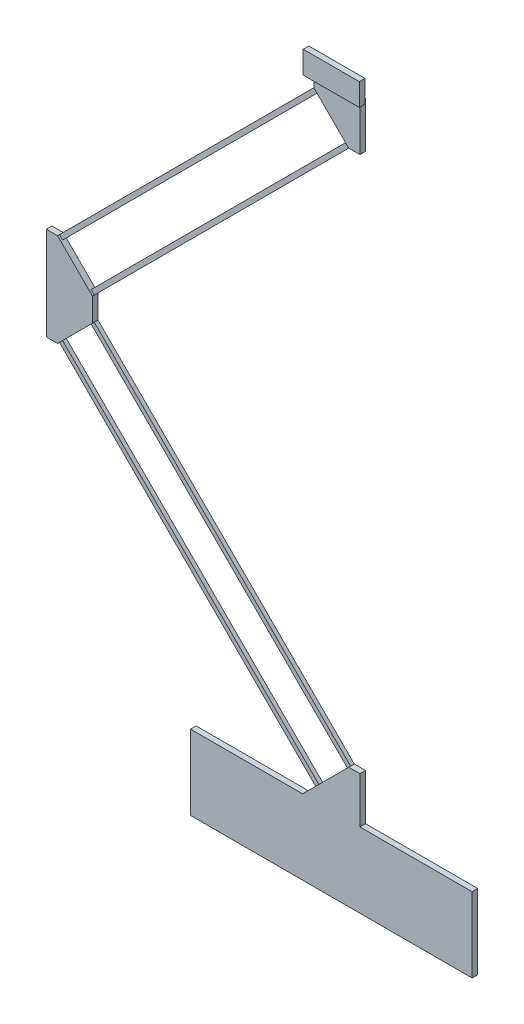
SolidWorks part; units mm, degrees
ref_plane "Front Plane" through (0, 0, 0) normal (0, 0, 1) x (1, 0, 0)
ref_plane "Top Plane" through (0, 0, 0) normal (0, 1, 0) x (1, 0, 0)
ref_plane "Right Plane" through (0, 0, 0) normal (1, 0, 0) x (0, 0, -1)
sketch "Sketch1" plane through (0, 0, 0) normal (0, 0, 1) x (1, 0, 0)
  line L0 (0, 0) -> (-84.8528, -84.8528)
  line L1 (0, 0) -> (-707.1068, 707.1068)
  line L2 (-84.8528, -84.8528) -> (-791.9596, 622.254)
  line L3 (-707.1068, 707.1068) -> (-791.9596, 622.254)
  line L4 (0, 0) -> (0, -84.8528) construction
  line L5 (0, -84.8528) -> (-84.8528, -84.8528) construction
  line L6 (-707.1068, 757.1068) -> (-791.9596, 841.9596)
  line L7 (-707.1068, 757.1068) -> (0, 1464.2136)
  line L8 (-791.9596, 841.9596) -> (-84.8528, 1549.0664)
  line L9 (0, 1464.2136) -> (-84.8528, 1549.0664)
  line L10 (-791.9596, 622.254) -> (-791.9596, 841.9596) construction
  line L11 (-707.1068, 707.1068) -> (-707.1068, 757.1068) construction
  line L12 (-707.1068, 732.1068) -> (-791.9596, 732.1068) construction
  point P12 (-1084.8528, 134.3981)
  point P13 (0, 0)
  point P14 (-1007.5691, 47.0134)
  point P15 (-1084.8528, 139.5688)
  point P16 (-1013.47, 286.1864)
  point P17 (0, 0)
  point P18 (152.8359, 878.8141)
  point P19 (39.4877, 109.7667)
  point P20 (-108.543, 914.8665)
  point P21 (-241.3606, 995.4355)
  point P22 (-38.2524, 1037.8463)
  point P23 (-117.549, 500.9334)
  point P24 (27.0087, 309.2042)
  point P25 (-1084.8522, 26.1452)
  point P26 (0, 99.2151)
  point P27 (-84.8528, 138.3372)
  point P28 (0, 0)
  point P29 (0, 0)
  point P30 (0, 0)
  point P31 (-998.3362, 431.8761)
  point P32 (656.1081, 992.4753)
  point P33 (-167.8514, 1497.8051)
  dimension "D1" = 1000
  dimension "D2" = 120
  dimension "D3" = 45
  dimension "D4" = 120
  dimension "D5" = 1000
  dimension "D6" = 90
  dimension "D7" = 50
  dimension "D8" = 45
  dimension "D9" = 45
extrude "Extrude-Thin1" add sketch "Sketch1" along normal blind 10 thin thin type mid plane wall 12
sketch "Sketch2" plane through (0, 0, 0) normal (0, 0, 1) x (1, 0, 0)
  line L0 (-815.4449, 856.9596) -> (-815.4449, 607.254)
  line L1 (-815.4449, 607.254) -> (-785.4449, 607.254)
  line L2 (-785.4449, 607.254) -> (-692.1068, 700.5921)
  line L3 (-692.1068, 700.5921) -> (-692.1068, 763.6215)
  line L4 (-692.1068, 763.6215) -> (-785.4449, 856.9596)
  line L5 (-785.4449, 856.9596) -> (-815.4449, 856.9596)
  line L6 (-785.4449, 607.254) -> (-785.4449, 856.9596) construction
  line L8 (-815.4449, 732.1068) -> (-692.1068, 732.1068)
  line L9 (-800.4449, 841.9596) -> (-800.4449, 856.9596) construction
  point P11 (0, 0)
  dimension "D1" = 15
  dimension "D2" = 15
  dimension "D3" = 15
  dimension "D4" = 15
  dimension "D5" = 15
extrude "Boss-Extrude1" add sketch "Sketch2" along normal blind 15 contours L8 L0 L1 L2 L3 | L0 L8 L3 L4 L5
sketch "Sketch3" plane through (0, 0, 0) normal (0, 0, 1) x (1, 0, 0)
  line L0 (-129.8528, -108.3381) -> (-6.5147, 15)
  line L1 (-6.5147, 15) -> (23.4853, 15)
  line L2 (23.4853, 15) -> (23.4853, -108.3381)
  line L3 (23.4853, -108.3381) -> (323.4853, -108.3381)
  line L4 (323.4853, -108.3381) -> (323.4853, -308.3381)
  line L5 (323.4853, -308.3381) -> (-429.8528, -308.3381)
  line L6 (-429.8528, -308.3381) -> (-429.8528, -108.3381)
  line L7 (-429.8528, -108.3381) -> (-129.8528, -108.3381)
  point P4 (-5.597, 15)
  dimension "D1" = 300
  dimension "D2" = 300
  dimension "D3" = 200
  dimension "D4" = 15
  dimension "D5" = 15
  dimension "D6" = 15
  dimension "D7" = 15
  dimension "D8" = 45
extrude "Boss-Extrude2" add sketch "Sketch3" along normal blind 15
sketch "Sketch4" plane through (0, 0, 0) normal (0, 0, 1) x (1, 0, 0)
  line L0 (-99.8528, 1572.5517) -> (-99.8528, 1542.5517)
  line L1 (-99.8528, 1542.5517) -> (-6.5147, 1449.2136)
  line L2 (-6.5147, 1449.2136) -> (23.4853, 1449.2136)
  line L3 (23.4853, 1449.2136) -> (23.4853, 1572.5517)
  line L4 (23.4853, 1572.5517) -> (-99.8528, 1572.5517)
  dimension "D1" = 45
  dimension "D2" = 15
  dimension "D3" = 15
  dimension "D4" = 30
  dimension "D5" = 15
  dimension "D6" = 30
extrude "Boss-Extrude3" add sketch "Sketch4" along normal blind 15
sketch "Sketch5" plane through (0, 0, 15) normal (0, 0, 1) x (1, 0, 0)
  line L0 (23.4853, 1572.5517) -> (-99.8528, 1572.5517) construction
  line L1 (-113.1838, 1572.5517) -> (36.8162, 1572.5517)
  line L2 (-113.1838, 1572.5517) -> (-113.1838, 1632.5517)
  line L3 (-113.1838, 1632.5517) -> (36.8162, 1632.5517)
  line L4 (36.8162, 1572.5517) -> (36.8162, 1632.5517)
  line L5 (-38.1838, 1572.5517) -> (-38.1838, 1632.5517) construction
  dimension "D1" = 150
  dimension "D2" = 60
extrude "Boss-Extrude4" add sketch "Sketch5" along normal blind 15 separate body
